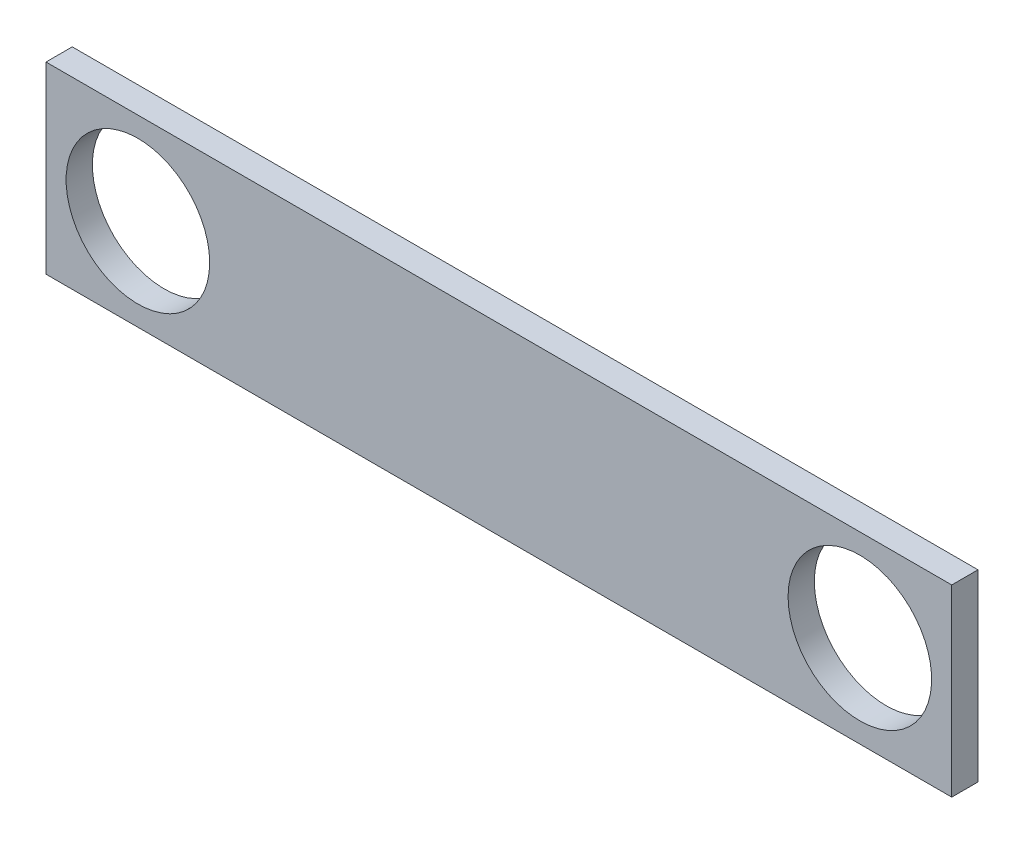
SolidWorks part; units mm, degrees
ref_plane "Płaszczyzna przednia" through (0, 0, 0) normal (0, 0, 1) x (1, 0, 0)
ref_plane "Płaszczyzna górna" through (0, 0, 0) normal (0, 1, 0) x (1, 0, 0)
ref_plane "Płaszczyzna prawa" through (0, 0, 0) normal (1, 0, 0) x (0, 0, -1)
sketch "Sketch1" plane through (0, 0, 0) normal (0, 0, 1) x (1, 0, 0)
  line L0 (0, -16.0168) -> (0, 22.9806) construction
  line L1 (-34.5, -7) -> (34.5, -7)
  line L2 (-34.5, -7) -> (-34.5, 7)
  line L3 (-34.5, 7) -> (34.5, 7)
  line L4 (34.5, -7) -> (34.5, 7)
  line L5 (-34.5, -7) -> (34.5, 7) construction
  line L6 (-34.5, 7) -> (34.5, -7) construction
  circle A0 centre (-27.5, 0) radius 5.4683
  circle A1 centre (27.5, 0) radius 5.4683
  point P0 (0, 0)
  dimension "D1" = 55
  dimension "D2" = 7
  dimension "D3" = 7
extrude "Boss-Extrude1" add sketch "Sketch1" along normal blind 2
equation "\"A\"=55"
equation "\"D1@Sketch1\"=\"A\""
